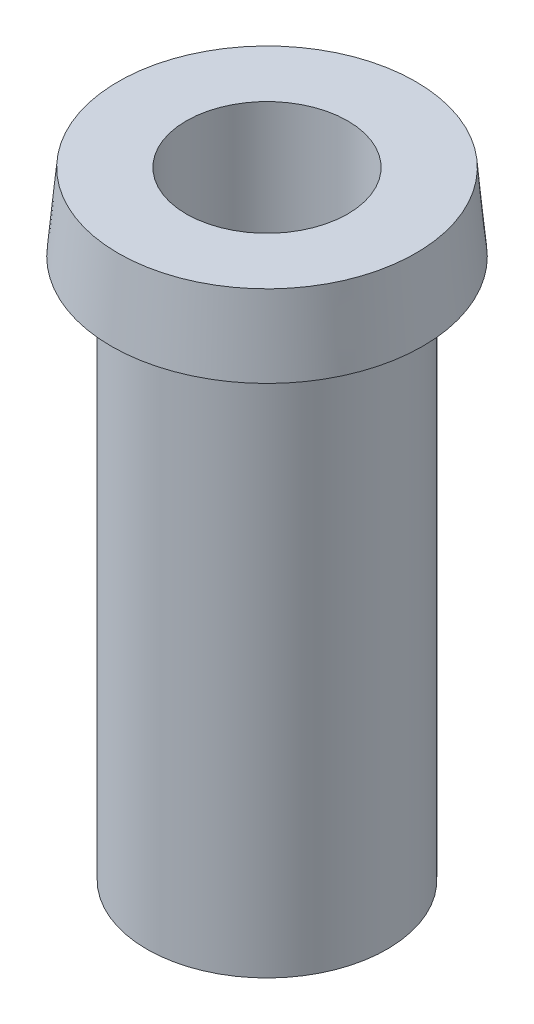
SolidWorks part; units mm, degrees
material "ABS"
ref_plane "Front Plane" through (0, 0, 0) normal (0, 0, 1) x (1, 0, 0)
ref_plane "Top Plane" through (0, 0, 0) normal (0, 1, 0) x (1, 0, 0)
ref_plane "Right Plane" through (0, 0, 0) normal (1, 0, 0) x (0, 0, -1)
other "Configuration Table"
sketch "Sketch1" plane through (0, 0, 0) normal (0, 1, 0) x (1, 0, 0)
  circle A0 centre (0, 0) radius 6.5024
  dimension "D1" = 13.0048
extrude "Boss-Extrude1" add sketch "Sketch1" along normal blind 33.401
sketch "Sketch2" plane through (0, 0, 0) normal (0, 1, 0) x (1, 0, 0)
  circle A0 centre (0, 0) radius 4.3688
  dimension "D1" = 8.7376
extrude "Cut-Extrude1" cut sketch "Sketch2" along normal blind 33.401
sketch "Sketch3" plane through (0, 0, 0) normal (0, 0, 1) x (1, 0, 0)
  line L0 (6.5024, 33.401) -> (8.0518, 33.401)
  line L1 (8.0518, 33.401) -> (8.4328, 29.2354)
  line L2 (8.4328, 29.2354) -> (6.5024, 29.2354)
  line L3 (6.5024, 0) -> (6.5024, 33.401) construction
  line L4 (6.5024, 29.2354) -> (6.5024, 33.401)
  line L5 (4.3688, 0) -> (4.3688, 33.401) construction
  dimension "D1" = 4.1656
  dimension "D2" = 3.683
  dimension "D3" = 4.064
revolve "Revolve2" add sketch "Sketch3" angle 360 about axis through (0, 33.401, 0) along (0, -1, 0)
